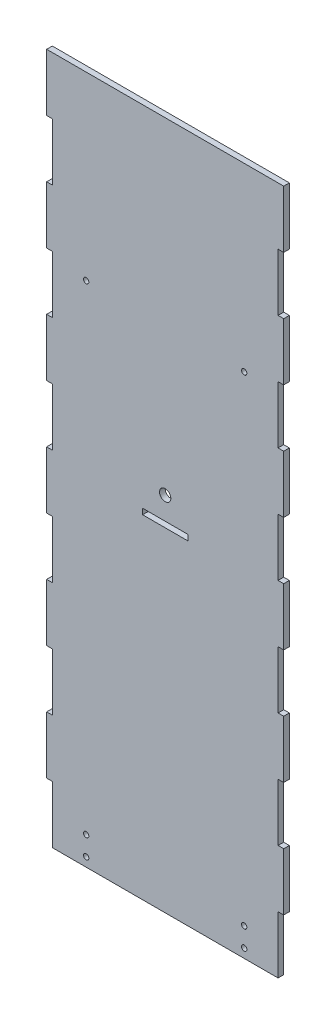
SolidWorks part; units mm, degrees
ref_plane "Front Plane" through (0, 0, 0) normal (0, 0, 1) x (1, 0, 0)
ref_plane "Top Plane" through (0, 0, 0) normal (0, 1, 0) x (1, 0, 0)
ref_plane "Right Plane" through (0, 0, 0) normal (1, 0, 0) x (0, 0, -1)
sketch "Sketch1" plane through (0, 0, 0) normal (0, 0, 1) x (1, 0, 0)
  line L0 (-63.5, 387.35) -> (-63.5, 0) construction
  line L1 (-66.675, 387.35) -> (66.675, 387.35)
  line L2 (-66.675, 387.35) -> (-66.675, 0)
  line L3 (-66.675, 0) -> (66.675, 0)
  line L4 (66.675, 387.35) -> (66.675, 0)
  line L5 (63.5, 387.35) -> (63.5, 0) construction
  line L6 (-63.5, 193.675) -> (63.5, 193.675) construction
  line L7 (-66.675, 6.35) -> (66.675, 6.35) construction
  line L8 (-66.675, 355.0708) -> (-66.675, 322.7917)
  line L9 (-66.675, 387.35) -> (-63.5, 387.35)
  line L10 (-66.675, 387.35) -> (-66.675, 355.0708)
  line L11 (-66.675, 355.0708) -> (-63.5, 355.0708)
  line L12 (-63.5, 387.35) -> (-63.5, 355.0708)
  line L13 (66.675, 387.35) -> (63.5, 387.35)
  line L14 (66.675, 387.35) -> (66.675, 355.0708)
  line L15 (66.675, 355.0708) -> (63.5, 355.0708)
  line L16 (63.5, 387.35) -> (63.5, 355.0708)
  line L17 (-66.675, 355.0708) -> (-63.5, 355.0708)
  line L18 (-63.5, 355.0708) -> (-63.5, 322.7917)
  line L19 (-66.675, 322.7917) -> (-63.5, 322.7917)
  line L20 (66.675, 355.0708) -> (66.675, 322.7917)
  line L21 (66.675, 355.0708) -> (63.5, 355.0708)
  line L22 (63.5, 355.0708) -> (63.5, 322.7917)
  line L23 (66.675, 322.7917) -> (63.5, 322.7917)
  line L24 (-66.675, 322.7917) -> (-66.675, 290.5125)
  line L25 (-66.675, 322.7917) -> (-63.5, 322.7917)
  line L26 (-63.5, 322.7917) -> (-63.5, 290.5125)
  line L27 (-66.675, 290.5125) -> (-63.5, 290.5125)
  line L28 (66.675, 322.7917) -> (66.675, 290.5125)
  line L29 (66.675, 322.7917) -> (63.5, 322.7917)
  line L30 (63.5, 322.7917) -> (63.5, 290.5125)
  line L31 (66.675, 290.5125) -> (63.5, 290.5125)
  line L32 (-66.675, 290.5125) -> (-66.675, 258.2333)
  line L33 (-66.675, 290.5125) -> (-63.5, 290.5125)
  line L34 (-63.5, 290.5125) -> (-63.5, 258.2333)
  line L35 (-66.675, 258.2333) -> (-63.5, 258.2333)
  line L36 (66.675, 290.5125) -> (66.675, 258.2333)
  line L37 (66.675, 290.5125) -> (63.5, 290.5125)
  line L38 (63.5, 290.5125) -> (63.5, 258.2333)
  line L39 (66.675, 258.2333) -> (63.5, 258.2333)
  line L40 (-66.675, 258.2333) -> (-66.675, 225.9542)
  line L41 (-66.675, 258.2333) -> (-63.5, 258.2333)
  line L42 (-63.5, 258.2333) -> (-63.5, 225.9542)
  line L43 (-66.675, 225.9542) -> (-63.5, 225.9542)
  line L44 (66.675, 258.2333) -> (66.675, 225.9542)
  line L45 (66.675, 258.2333) -> (63.5, 258.2333)
  line L46 (63.5, 258.2333) -> (63.5, 225.9542)
  line L47 (66.675, 225.9542) -> (63.5, 225.9542)
  line L48 (-66.675, 225.9542) -> (-66.675, 193.675)
  line L49 (-66.675, 225.9542) -> (-63.5, 225.9542)
  line L50 (-63.5, 225.9542) -> (-63.5, 193.675)
  line L51 (-66.675, 193.675) -> (-63.5, 193.675)
  line L52 (66.675, 225.9542) -> (66.675, 193.675)
  line L53 (66.675, 225.9542) -> (63.5, 225.9542)
  line L54 (63.5, 225.9542) -> (63.5, 193.675)
  line L55 (66.675, 193.675) -> (63.5, 193.675)
  line L56 (-66.675, 193.675) -> (-66.675, 161.3958)
  line L57 (-66.675, 193.675) -> (-63.5, 193.675)
  line L58 (-63.5, 193.675) -> (-63.5, 161.3958)
  line L59 (-66.675, 161.3958) -> (-63.5, 161.3958)
  line L60 (66.675, 193.675) -> (66.675, 161.3958)
  line L61 (66.675, 193.675) -> (63.5, 193.675)
  line L62 (63.5, 193.675) -> (63.5, 161.3958)
  line L63 (66.675, 161.3958) -> (63.5, 161.3958)
  line L64 (-66.675, 161.3958) -> (-66.675, 129.1167)
  line L65 (-66.675, 161.3958) -> (-63.5, 161.3958)
  line L66 (-63.5, 161.3958) -> (-63.5, 129.1167)
  line L67 (-66.675, 129.1167) -> (-63.5, 129.1167)
  line L68 (66.675, 161.3958) -> (66.675, 129.1167)
  line L69 (66.675, 161.3958) -> (63.5, 161.3958)
  line L70 (63.5, 161.3958) -> (63.5, 129.1167)
  line L71 (66.675, 129.1167) -> (63.5, 129.1167)
  line L72 (-66.675, 129.1167) -> (-66.675, 96.8375)
  line L73 (-66.675, 129.1167) -> (-63.5, 129.1167)
  line L74 (-63.5, 129.1167) -> (-63.5, 96.8375)
  line L75 (-66.675, 96.8375) -> (-63.5, 96.8375)
  line L76 (66.675, 129.1167) -> (66.675, 96.8375)
  line L77 (66.675, 129.1167) -> (63.5, 129.1167)
  line L78 (63.5, 129.1167) -> (63.5, 96.8375)
  line L79 (66.675, 96.8375) -> (63.5, 96.8375)
  line L80 (-66.675, 96.8375) -> (-66.675, 64.5583)
  line L81 (-66.675, 96.8375) -> (-63.5, 96.8375)
  line L82 (-63.5, 96.8375) -> (-63.5, 64.5583)
  line L83 (-66.675, 64.5583) -> (-63.5, 64.5583)
  line L84 (66.675, 96.8375) -> (66.675, 64.5583)
  line L85 (66.675, 96.8375) -> (63.5, 96.8375)
  line L86 (63.5, 96.8375) -> (63.5, 64.5583)
  line L87 (66.675, 64.5583) -> (63.5, 64.5583)
  line L88 (-66.675, 64.5583) -> (-66.675, 32.2792)
  line L89 (-66.675, 64.5583) -> (-63.5, 64.5583)
  line L90 (-63.5, 64.5583) -> (-63.5, 32.2792)
  line L91 (-66.675, 32.2792) -> (-63.5, 32.2792)
  line L92 (66.675, 64.5583) -> (66.675, 32.2792)
  line L93 (66.675, 64.5583) -> (63.5, 64.5583)
  line L94 (63.5, 64.5583) -> (63.5, 32.2792)
  line L95 (66.675, 32.2792) -> (63.5, 32.2792)
  line L96 (-66.675, 32.2792) -> (-66.675, 0)
  line L97 (-66.675, 32.2792) -> (-63.5, 32.2792)
  line L98 (-63.5, 32.2792) -> (-63.5, 0)
  line L99 (-66.675, 0) -> (-63.5, 0)
  line L100 (66.675, 32.2792) -> (66.675, 0)
  line L101 (66.675, 32.2792) -> (63.5, 32.2792)
  line L102 (63.5, 32.2792) -> (63.5, 0)
  line L103 (66.675, 0) -> (63.5, 0)
  line L105 (-12.7, 190.754) -> (12.7, 190.754)
  line L106 (-12.7, 190.754) -> (-12.7, 187.579)
  line L107 (-12.7, 187.579) -> (12.7, 187.579)
  line L108 (12.7, 190.754) -> (12.7, 187.579)
  circle A0 centre (0, 203.454) radius 3.175
  point P4 (0, 0)
  point P12 (0, 193.675)
  point P114 (12.0728, 203.454)
  point P115 (0, 190.754)
  point P116 (0, 187.579)
  dimension "D10" = 6.35
  dimension "D1" = 127
  dimension "D2" = 3.175
  dimension "D3" = 387.35
  dimension "D4" = 6.35
  dimension "D6" = 32.2792
  dimension "D7" = 187.579
  dimension "D8" = 3.175
  dimension "D9" = 12.7
  dimension "D11" = 25.4
  dimension "D5" = 12
extrude "Boss-Extrude1" add sketch "Sketch1" along normal blind 3.175 contours L102 L94 L86 L78 L70 L62 L54 L46 L38 L30 L22 L16 L1 L12 L18 L26 L34 L42 L50 L58 L66 L74 L82 L90 L98 L3 A0 L105 L108 L107 L106 | L12 L1 L2 L11 | L2 L27 L26 L19 | L2 L43 L42 L35 | L2 L59 L58 L51 | L1 L16 L15 L4 | L31 L4 L23 L30 | L47 L4 L39 L46 | L63 L4 L55 L62 | L79 L4 L71 L78 | L2 L75 L74 L67 | L2 L91 L90 L83 | L95 L4 L87 L94
sketch "Sketch2" plane through (0, 0, 3.175) normal (0, 0, 1) x (1, 0, 0)
  line L0 (-44.45, 285.75) -> (44.45, 285.75) construction
  line L1 (44.45, 285.75) -> (44.45, 15.875) construction
  line L2 (44.45, 15.875) -> (-44.45, 15.875) construction
  line L3 (-44.45, 15.875) -> (-44.45, 285.75) construction
  line L4 (-66.675, 387.35) -> (66.675, 387.35) construction
  line L5 (-66.675, 322.7917) -> (-66.675, 290.5125) construction
  line L6 (-63.5, 0) -> (63.5, 0) construction
  circle A0 centre (-44.45, 285.75) radius 1.5
  circle A1 centre (44.45, 285.75) radius 1.5
  circle A2 centre (-44.45, 15.875) radius 1.5
  circle A3 centre (44.45, 15.875) radius 1.5
  circle A4 centre (-44.45, 5.08) radius 1.5
  circle A5 centre (44.45, 5.08) radius 1.5
  point P12 (0, 0)
  point P13 (0, 285.75)
  point P17 (0, 0)
  point P22 (0, 0)
  dimension "D1" = 3
  dimension "D2" = 101.6
  dimension "D3" = 22.225
  dimension "D4" = 15.875
  dimension "D5" = 5.08
extrude "Cut-Extrude1" cut sketch "Sketch2" against normal through all
equation "\"wallThickness\"= .125in"
equation "\"bottomThickness\"= .25"
equation "\"D2@Sketch1\"=\"wallThickness\""
equation "\"D3@Sketch1\"=\"bottomThickness\"+\"chamberHeight\""
equation "\"D4@Sketch1\"=\"bottomThickness\""
equation "\"chamberHeight\"= 15"
equation "\"D6@Sketch1\"=\"D3@Sketch1\"/\"D5@Sketch1\""
equation "\"D8@Sketch1\"=\"wallThickness\""
equation "\"D1@Boss-Extrude1\"=\"wallThickness\""
